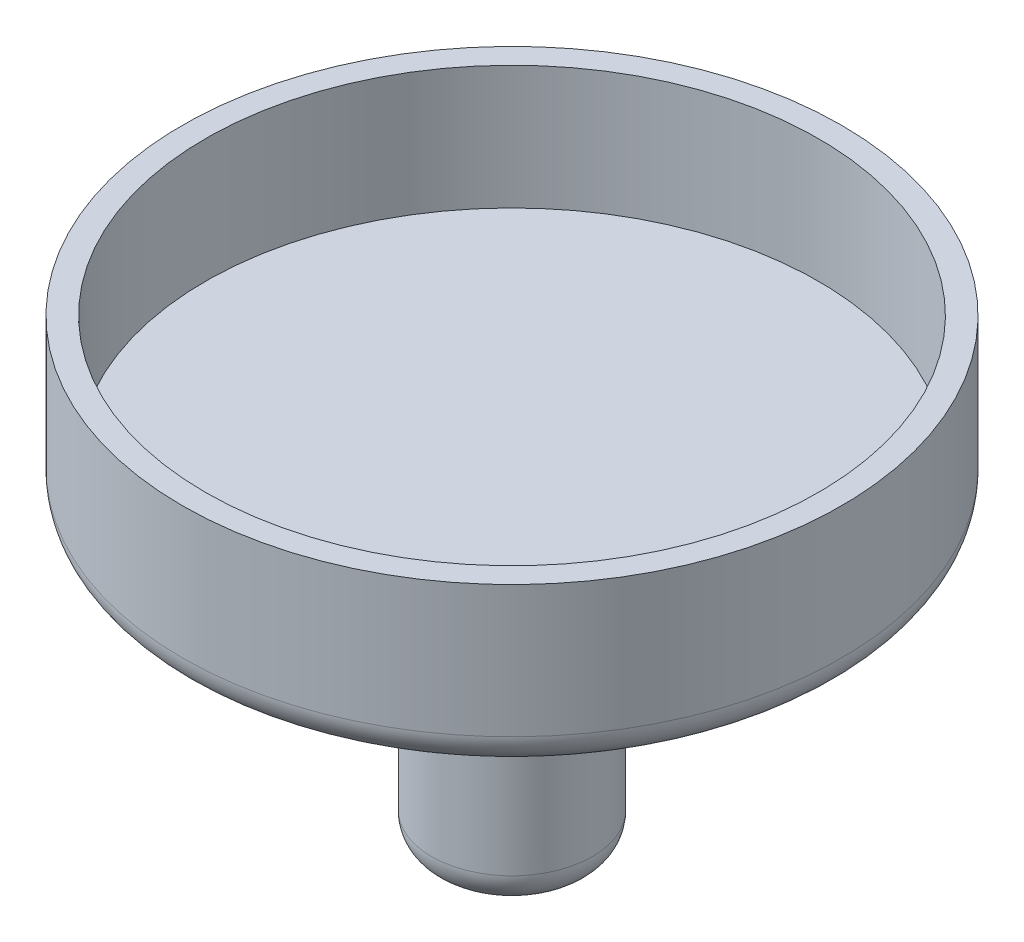
SolidWorks part; units mm, degrees
ref_plane "Front Plane" through (0, 0, 0) normal (0, 0, 1) x (1, 0, 0)
ref_plane "Top Plane" through (0, 0, 0) normal (0, 1, 0) x (1, 0, 0)
ref_plane "Right Plane" through (0, 0, 0) normal (1, 0, 0) x (0, 0, -1)
sketch "Sketch1" plane through (0, 0, 0) normal (0, 1, 0) x (1, 0, 0)
  circle A0 centre (0, 0) radius 12.7
extrude "Boss-Extrude1" add sketch "Sketch1" along normal blind 6.35 contours A0
sketch "Sketch2" plane through (0, 6.35, 0) normal (0, 1, 0) x (1, 0, 0)
  circle A0 centre (0, 0) radius 11.811
extrude "Cut-Extrude1" cut sketch "Sketch2" against normal blind 4.7625 contours A0
sketch "Sketch3" plane through (0, 0, 0) normal (0, -1, 0) x (1, 0, 0)
  circle A0 centre (0, 0) radius 3.0988
extrude "Boss-Extrude2" add sketch "Sketch3" along normal blind 11.43
fillet "Fillet1" radius 1.27 3 edges at (0, 0, 12.7) (0, 0, -3.0988) (0, -11.43, -3.0988)
